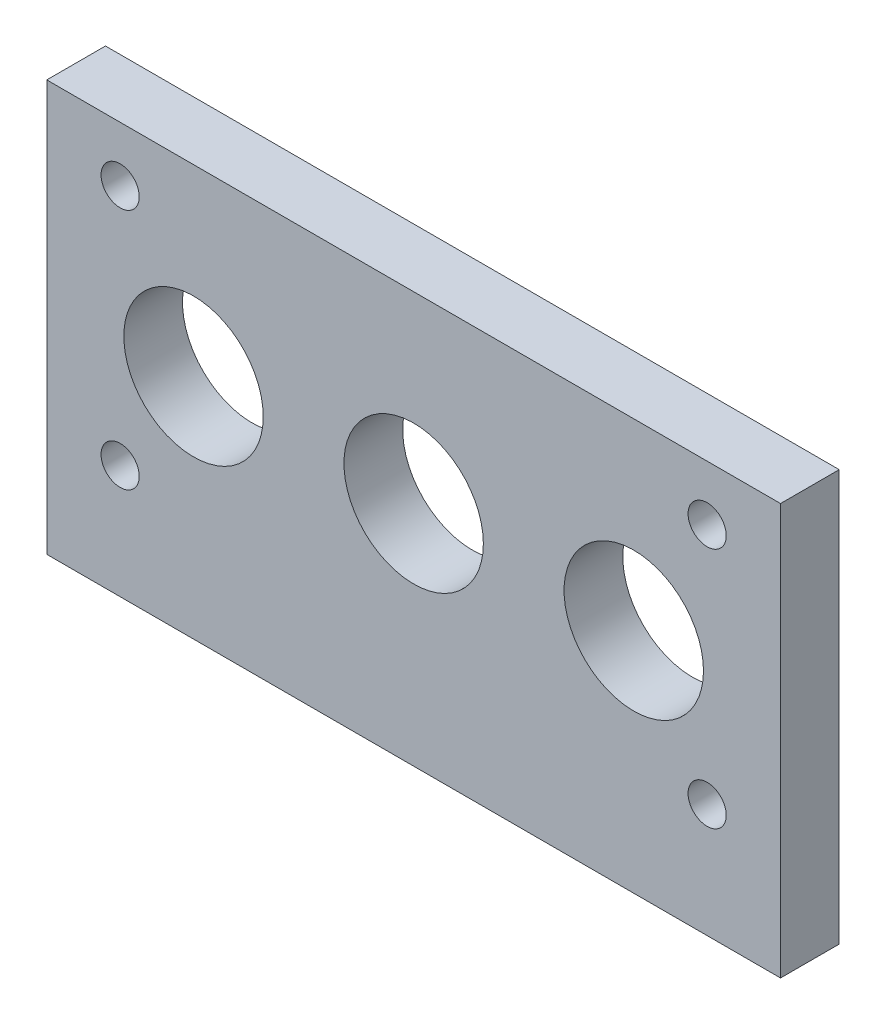
SolidWorks part; units mm, degrees
ref_plane "Ön Düzlem" through (0, 0, 0) normal (0, 0, 1) x (1, 0, 0)
ref_plane "Üst Düzlem" through (0, 0, 0) normal (0, 1, 0) x (1, 0, 0)
ref_plane "Sağ Düzlem" through (0, 0, 0) normal (1, 0, 0) x (0, 0, -1)
sketch "Çizim1" plane through (0, 0, 0) normal (0, 0, 1) x (1, 0, 0)
  line L1 (-52.0311, 28.2577) -> (47.9689, 28.2577)
  line L2 (-52.0311, 28.2577) -> (-52.0311, -27.7423)
  line L3 (-52.0311, -27.7423) -> (47.9689, -27.7423)
  line L4 (47.9689, 28.2577) -> (47.9689, -27.7423)
  circle A0 centre (-32.0311, 3.2577) radius 9.5
  circle A1 centre (27.9689, 3.2577) radius 9.5
  circle A2 centre (-2.0311, 3.2577) radius 9.5
  dimension "D3" = 19
  dimension "19" = 19
  dimension "D4" = 20
  dimension "D5" = 20
  dimension "D6" = 25
  dimension "D7" = 25
  dimension "D8" = 25
  dimension "D9" = 19
  dimension "D1" = 100
  dimension "D2" = 56
extrude "Yükseklik-Ekstrüzyon1" add sketch "Çizim1" along normal blind 8
sketch "Çizim2" plane through (0, 0, 0) normal (0, 0, -1) x (-1, 0, 0)
  circle A0 centre (-37.9689, 20.7577) radius 2.6
  circle A1 centre (-37.9689, -12.2423) radius 2.6
  circle A2 centre (42.0311, -12.2423) radius 2.6
  circle A3 centre (42.0311, 20.7577) radius 2.6
extrude "Kes-Ekstrüzyon1" cut sketch "Çizim2" against normal blind 10
